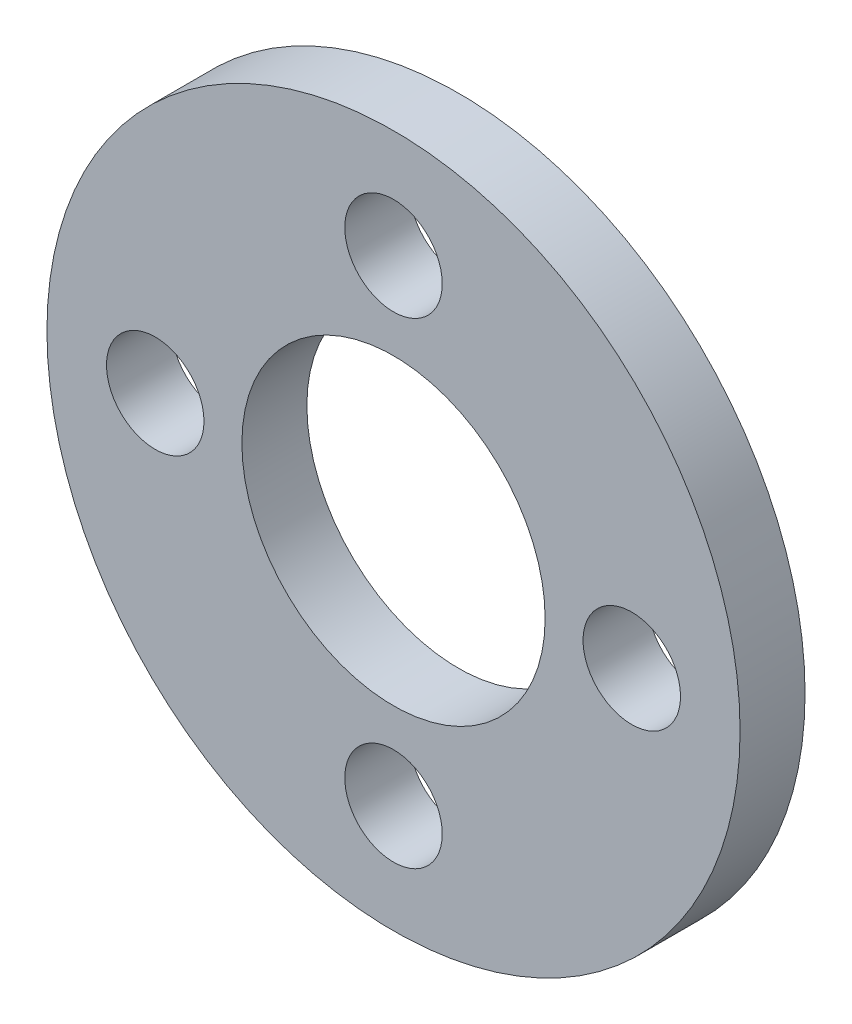
SolidWorks part; units mm, degrees
material "PLA+"
ref_plane "Front Plane" through (0, 0, 0) normal (0, 0, 1) x (1, 0, 0)
ref_plane "Top Plane" through (0, 0, 0) normal (0, 1, 0) x (1, 0, 0)
ref_plane "Right Plane" through (0, 0, 0) normal (1, 0, 0) x (0, 0, -1)
sketch "Sketch1" plane through (0, 0, 0) normal (0, 0, 1) x (1, 0, 0)
  circle A0 centre (0, 0) radius 16
  circle A1 centre (0, 0) radius 7
  circle A2 centre (0, 0) radius 11 construction
  circle A3 centre (11, 0) radius 2.25
  circle A4 centre (0, 11) radius 2.25
  circle A5 centre (-11, 0) radius 2.25
  circle A6 centre (0, -11) radius 2.25
  dimension "D1" = 22
  dimension "D2" = 14
  dimension "D3" = 32
  dimension "D4" = 4.5
extrude "Boss-Extrude1" add sketch "Sketch1" along normal blind 3
